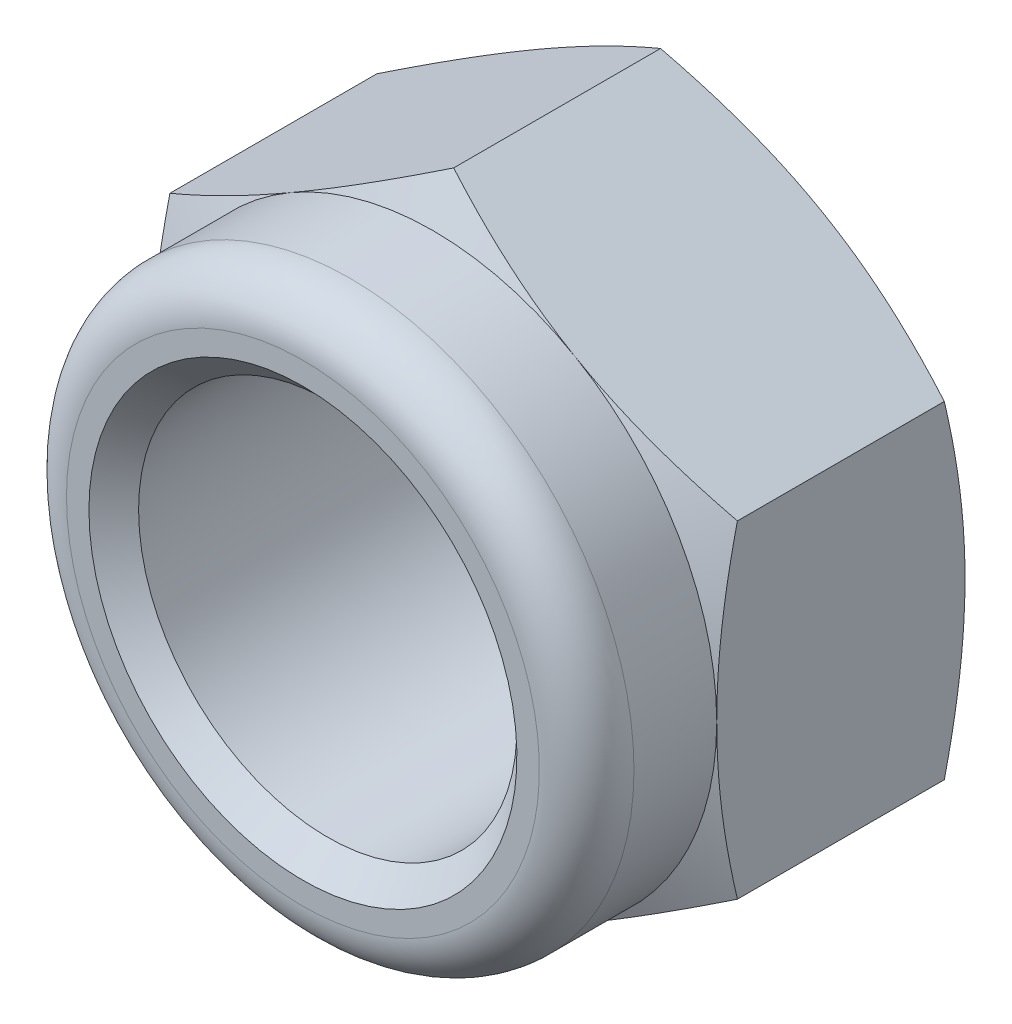
SolidWorks part; units mm, degrees
material "Plain Carbon Steel"
ref_plane "Front Plane" through (0, 0, 0) normal (0, 0, 1) x (1, 0, 0)
ref_plane "Top Plane" through (0, 0, 0) normal (0, 1, 0) x (1, 0, 0)
ref_plane "Right Plane" through (0, 0, 0) normal (1, 0, 0) x (0, 0, -1)
sketch "Sketch1" plane through (0, 0, 0) normal (0, 0, 1) x (1, 0, 0)
  line L1 (0, -13.8564) -> (12, -6.9282)
  line L2 (12, -6.9282) -> (12, 6.9282)
  line L3 (12, 6.9282) -> (0, 13.8564)
  line L4 (0, 13.8564) -> (-12, 6.9282)
  line L5 (-12, 6.9282) -> (-12, -6.9282)
  line L6 (-12, -6.9282) -> (0, -13.8564)
  circle A0 centre (0, 0) radius 12 construction
  circle A1 centre (0, 0) radius 8
  dimension "D2" = 16
  dimension "D1" = 24
extrude "Boss-Extrude1" add sketch "Sketch1" along normal blind 10.5
sketch "Sketch3" plane through (0, 0, 0) normal (0, 1, 0) x (0, 0, -1)
  line L0 (-10.5, 12) -> (-14, 12)
  line L1 (-10.5, -12) -> (-10.5, 0) construction
  line L2 (-16, 10) -> (-16, 8)
  line L3 (-16, 8) -> (-10.5, 8)
  line L5 (-10.5, 8) -> (-10.5, 12)
  line L6 (0, 0) -> (-2.4, 0) construction
  arc A0 (-14, 12) -> (-16, 10) centre (-14, 10) ccw
  dimension "D1" = 2
  dimension "D2" = 16
revolve "Revolve1" add sketch "Sketch3" angle 360 about L6
sketch "Sketch2" plane through (0, 0, 0) normal (1, 0, 0) x (0, 0, -1)
  line L0 (-10.5, 13.8564) -> (-10.5, 12)
  line L1 (-10.5, 6.9282) -> (-10.5, 10.3923) construction
  line L2 (-10.5, 12) -> (-9.625, 13.8564)
  line L3 (-10.5, 13.8564) -> (0, 13.8564) construction
  line L4 (-9.625, 13.8564) -> (-10.5, 13.8564)
  line L5 (-0.875, 13.8564) -> (0, 13.8564)
  line L6 (0, 13.8564) -> (0, 12)
  line L7 (0, 6.9282) -> (0, 13.8564) construction
  line L8 (0, 12) -> (-0.875, 13.8564)
  line L9 (-9.625, 13.8564) -> (-8.75, 13.8564) construction
  line L10 (-8.75, 13.8564) -> (-7.875, 13.8564) construction
  line L11 (-7.875, 13.8564) -> (-7, 13.8564) construction
  line L12 (-7, 13.8564) -> (-6.125, 13.8564) construction
  line L13 (-6.125, 13.8564) -> (-5.25, 13.8564) construction
  line L14 (-5.25, 13.8564) -> (-4.375, 13.8564) construction
  line L15 (-4.375, 13.8564) -> (-3.5, 13.8564) construction
  line L16 (-3.5, 13.8564) -> (-2.625, 13.8564) construction
  line L17 (-2.625, 13.8564) -> (-1.75, 13.8564) construction
  line L18 (0, 0) -> (-2.4, 0) construction
  line L20 (-16, 8) -> (-14.95, 8)
  line L21 (-14.95, 8) -> (-16, 9.05)
  line L22 (-16, 9.05) -> (-16, 8)
  line L23 (0, 8) -> (-1.05, 8)
  line L24 (0, -6.9282) -> (0, 6.9282) construction
  line L25 (-1.05, 8) -> (0, 9.05)
  line L26 (0, 9.05) -> (0, 8)
  line L27 (-16, 10) -> (-16, -10) construction
  line L28 (-8.4, 8) -> (-9.45, 8) construction
  line L29 (-9.45, 8) -> (-10.5, 8) construction
  line L30 (-8.4, 8) -> (-7.35, 8) construction
  line L31 (-7.35, 8) -> (-6.3, 8) construction
  line L32 (-6.3, 8) -> (-5.25, 8) construction
  line L33 (-5.25, 8) -> (-4.2, 8) construction
  line L34 (-4.2, 8) -> (-3.15, 8) construction
  line L35 (-3.15, 8) -> (-2.1, 8) construction
  line L36 (-2.1, 8) -> (-1.05, 8) construction
  line L37 (-1.75, 13.8564) -> (-0.875, 13.8564) construction
  line L38 (-10.5, 0) -> (-10.5, 6.9282) construction
  dimension "D1" = 24
revolve "Cut-Revolve1" cut sketch "Sketch2" angle 360 about L18
